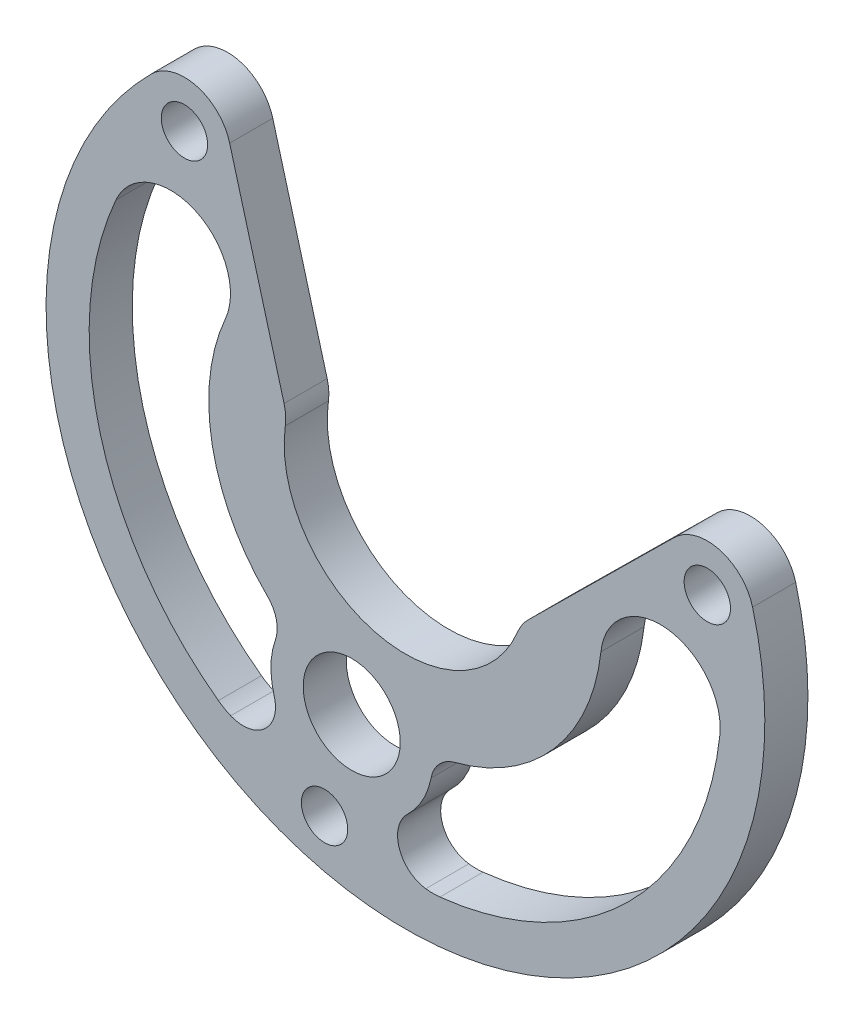
SolidWorks part; units mm, degrees
material "6061 Alloy"
ref_plane "Front Plane" through (0, 0, 0) normal (0, 0, 1) x (1, 0, 0)
ref_plane "Top Plane" through (0, 0, 0) normal (0, 1, 0) x (1, 0, 0)
ref_plane "Right Plane" through (0, 0, 0) normal (1, 0, 0) x (0, 0, -1)
sketch "Sketch1" plane through (0, 0, 0) normal (0, 0, 1) x (1, 0, 0)
  line L0 (169.0712, 34.6) -> (155.4979, 21.1875)
  line L1 (132.8544, 27.2548) -> (127.8058, 45.657)
  line L2 (144.1169, 24) -> (173.1367, 52.6759) construction
  arc A0 (177.4669, 23.9998) -> (120.5529, 47.6) centre (144.1169, 24) ccw construction
  arc A1 (120.5349, 47.582) -> (176.3305, 32.6316) centre (144.1169, 24) ccw
  circle A2 centre (136.6111, -4.0118) radius 2.15 construction
  circle A3 centre (172.1287, 31.5058) radius 2.15 construction
  circle A4 centre (123.6108, 44.5061) radius 2.15 construction
  circle A5 centre (144.1169, 24) radius 11.25 construction
  arc A6 (146.1075, 5.8589) -> (147.3182, -5.1749) centre (146.7128, 0.342) ccw construction
  arc A7 (147.3182, -5.1749) -> (173.2918, 20.7987) centre (144.1169, 24) ccw construction
  arc A8 (146.1075, 5.8589) -> (162.258, 22.0094) centre (144.1169, 24) ccw construction
  arc A9 (173.2918, 20.7987) -> (162.258, 22.0094) centre (167.7749, 21.4041) ccw construction
  arc A10 (126.757, 0.3344) -> (133.3224, 9.2846) centre (130.0397, 4.8095) ccw construction
  arc A11 (117.25, 35.8151) -> (126.757, 0.3344) centre (144.1169, 24) ccw construction
  arc A12 (127.4109, 31.3467) -> (133.3224, 9.2846) centre (144.1169, 24) ccw construction
  arc A13 (127.4109, 31.3467) -> (117.25, 35.8151) centre (122.3305, 33.5809) ccw construction
  arc A14 (127.4109, 31.3467) -> (117.25, 35.8151) centre (122.3305, 33.5809) ccw
  arc A15 (127.4109, 31.3467) -> (133.3224, 9.2846) centre (144.1169, 24) ccw
  arc A16 (117.25, 35.8151) -> (126.757, 0.3344) centre (144.1169, 24) ccw
  arc A17 (126.757, 0.3344) -> (133.3224, 9.2846) centre (130.0397, 4.8095) ccw
  arc A18 (173.2918, 20.7987) -> (162.258, 22.0094) centre (167.7749, 21.4041) ccw
  arc A19 (146.1075, 5.8589) -> (162.258, 22.0094) centre (144.1169, 24) ccw
  arc A20 (147.3182, -5.1749) -> (173.2918, 20.7987) centre (144.1169, 24) ccw
  arc A21 (146.1075, 5.8589) -> (147.3182, -5.1749) centre (146.7128, 0.342) ccw
  arc A22 (132.9697, 25.5173) -> (154.5293, 19.7404) centre (144.1169, 24) ccw
  circle A23 centre (123.6108, 44.5061) radius 2.15
  circle A24 centre (172.1287, 31.5058) radius 2.15
  circle A25 centre (136.6111, -4.0118) radius 2.15
  arc A26 (176.3305, 32.6316) -> (169.0712, 34.6) centre (172.1287, 31.5058) ccw
  arc A27 (155.4979, 21.1875) -> (154.5293, 19.7404) centre (158.5554, 18.0933) ccw
  arc A28 (132.9697, 25.5173) -> (132.8544, 27.2548) centre (128.6594, 26.104) ccw
  arc A29 (120.5349, 47.582) -> (127.8058, 45.657) centre (123.6108, 44.5061) cw
  dimension "D1" = 10
extrude "Boss-Extrude1" add sketch "Sketch1" along normal blind 4
sketch "Sketch2" plane through (0, 0, 0) normal (0, 0, -1) x (-1, 0, 0)
  circle A0 centre (-139.1346, 5.4059) radius 4.5
  dimension "D1" = 9
extrude "Cut-Extrude1" cut sketch "Sketch2" against normal blind 10
sketch "Sketch3" plane through (0, 0, 4) normal (0, 0, 1) x (1, 0, 0)
  arc A0 (143.6109, 4.9442) -> (135.0272, 7.2442) centre (139.1346, 5.4059) ccw construction
  circle A1 centre (139.1346, 5.4059) radius 4.5
  circle A2 centre (139.1346, 5.4059) radius 7.5
  dimension "D1" = 15
extrude "Boss-Extrude2" add sketch "Sketch3" against normal blind 4
fillet "Fillet1" radius 3 4 edges at (133.4927, 0.4644, 2) (132.9129, 9.594, 2) (141.5499, -1.6945, 2) (146.6168, 5.922, 2)
